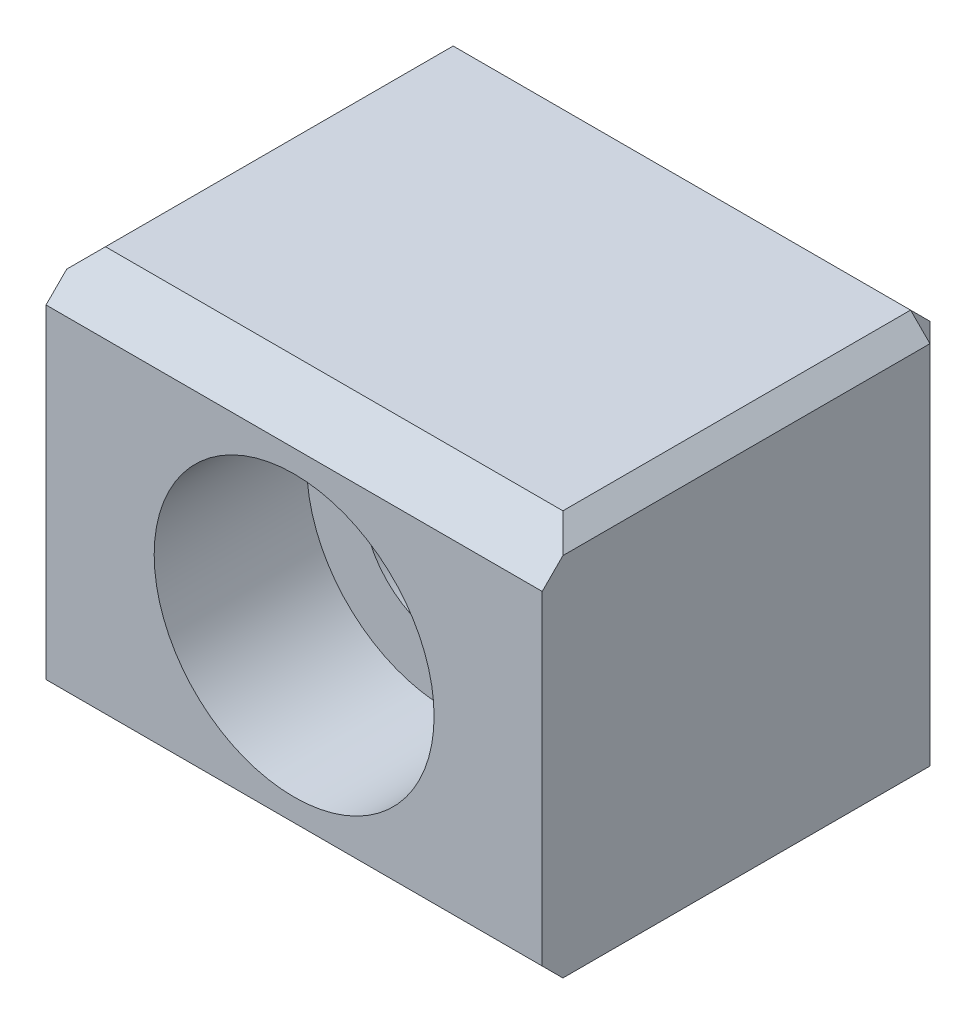
SolidWorks part; units mm, degrees
material "Plain Carbon Steel"
ref_plane "Front Plane" through (0, 0, 0) normal (0, 0, 1) x (1, 0, 0)
ref_plane "Top Plane" through (0, 0, 0) normal (0, 1, 0) x (1, 0, 0)
ref_plane "Right Plane" through (0, 0, 0) normal (1, 0, 0) x (0, 0, -1)
sketch "Sketch1" plane through (0, 0, 0) normal (0, 1, 0) x (1, 0, 0)
  line L1 (-9.75, 8) -> (9.75, 8)
  line L2 (-9.75, 8) -> (-9.75, -8)
  line L3 (-9.75, -8) -> (9.75, -8)
  line L4 (9.75, 8) -> (9.75, -8)
  dimension "D1" = 16
  dimension "D2" = 19.5
  dimension "D3" = 8
  dimension "D4" = 9.75
extrude "Extrude1" add sketch "Sketch1" along normal mid plane 15.9
hole_wizard "CBORE for M6 SHCS1" positions "Sketch5" profile "Sketch4" counterbore size "M6" standard "Ansi Metric" end condition through all
sketch "Sketch5" plane through (0, 0, 8) normal (0, 0, 1) x (1, 0, 0)
  point P1 (0, 0)
sketch "Sketch4" plane through (0, 0, 8) normal (1, 0, 0) x (0, -1, 0)
  line L0 (0, 0) -> (0, 16)
  line L1 (0, 16) -> (3.3, 16)
  line L3 (3.3, 16) -> (3.3, 6)
  line L4 (3.3, 6) -> (5.5, 6)
  line L5 (5.5, 6) -> (5.5, 0)
  line L7 (5.5, 0) -> (0, 0)
  line L11 (0, -6.35) -> (0, 107.95) construction
  dimension "Thru Hole Dia." = 6.6
  dimension "Thru Hole Depth" = 16
  dimension "C'Bore Dia." = 11
  dimension "C'Bore Depth" = 6
chamfer "Chamfer1" distance 0.762 angle 45 8 edges at (0, -7.95, -8) (-9.75, -7.95, 0) (-9.75, 0, -8) (9.75, -7.95, 0) (9.75, 0, -8) (9.75, 7.95, 0) (0, 7.95, -8) (-9.75, 7.95, 0)
chamfer "Chamfer2" distance 1.5748 angle 45 2 edges at (0, -7.95, 8) (0, 7.95, 8)
other "Freeze***"
equation "\"D3@Sketch1\" = \"D1@Sketch1\"/2"
equation "\"D4@Sketch1\" = \"D2@Sketch1\"/2"
